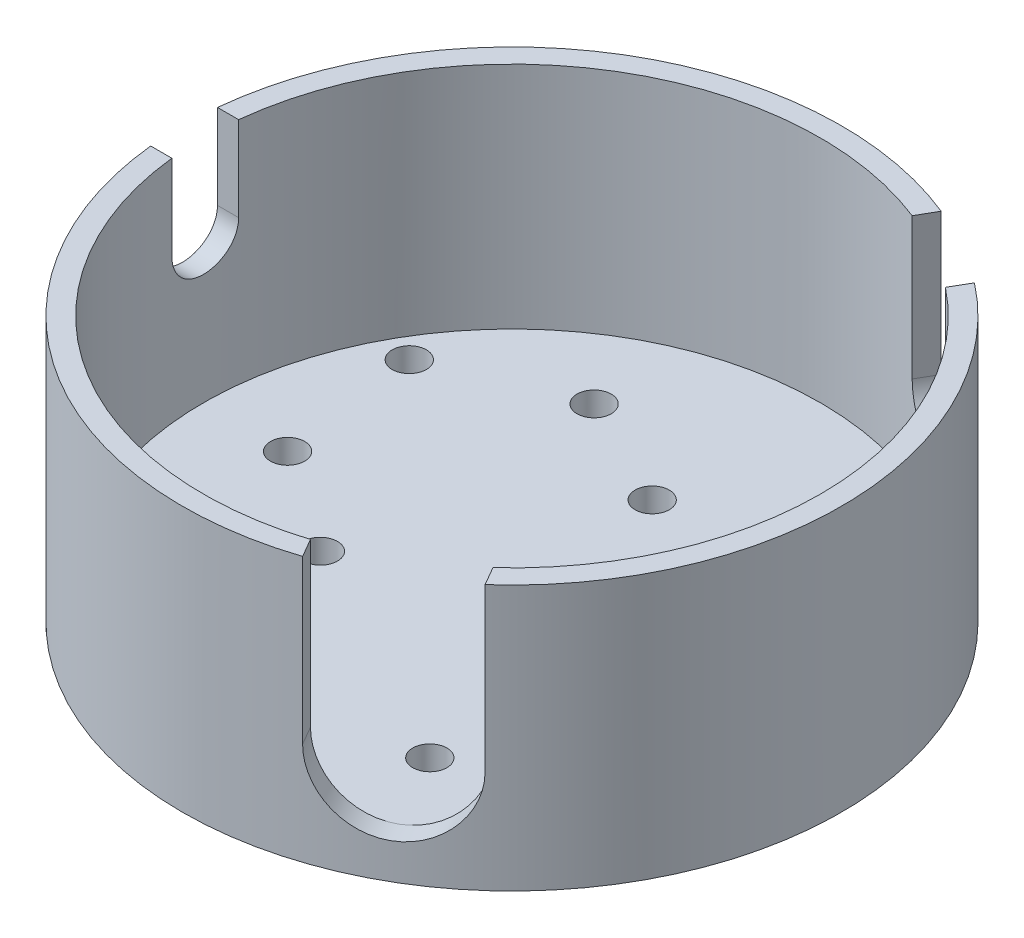
SolidWorks part; units mm, degrees
material "6061-T6 (SS)"
ref_plane "Front Plane" through (0, 0, 0) normal (0, 0, 1) x (1, 0, 0)
ref_plane "Top Plane" through (0, 0, 0) normal (0, 1, 0) x (1, 0, 0)
ref_plane "Right Plane" through (0, 0, 0) normal (1, 0, 0) x (0, 0, -1)
sketch "Sketch1" plane through (0, 0, 0) normal (0, 1, 0) x (1, 0, 0)
  circle A0 centre (0, 0) radius 23.5
  dimension "D1" = 47
extrude "Boss-Extrude1" add sketch "Sketch1" along normal blind 2.54
sketch "Sketch2" plane through (0, 2.54, 0) normal (0, 1, 0) x (1, 0, 0)
  circle A0 centre (0, 0) radius 10 construction
  circle A1 centre (0, 0) radius 23.5
  circle A2 centre (0, 0) radius 23.5
  point P1 (0, 10)
  point P5 (8.6603, -5)
  point P8 (-8.6603, -5)
  dimension "D2" = 20
  dimension "D1" = 0
  dimension "D3" = 3
hole_wizard "#2 Clearance Hole2" positions "3DSketch1" profile "Sketch3" hole size "#2" standard "Ansi Inch" end condition through all
sketch3d "3DSketch1"
  point P0 (0, 2.54, -10)
  point P3 (8.6603, 2.54, 5)
  point P6 (-8.6603, 2.54, 5)
sketch "Sketch3" plane through (0, 2.54, -10) normal (1, 0, 0) x (0, 0, 1)
  line L0 (0, 0) -> (0, 2.54)
  line L1 (0, 2.54) -> (1.2192, 2.54)
  line L2 (1.2192, 2.54) -> (1.2192, 0)
  line L5 (1.2192, 0) -> (0, 0)
  line L11 (0, -6.35) -> (0, 107.95) construction
  dimension "Thru Hole Dia." = 2.4384
  dimension "Thru Hole Depth" = 2.54
sketch "Sketch4" plane through (0, 2.54, 0) normal (0, 1, 0) x (1, 0, 0)
  circle A0 centre (0, 0) radius 22
  circle A1 centre (0, 0) radius 23.5
  circle A2 centre (0, 0) radius 23.5
  dimension "D1" = 0
  dimension "D2" = 1.5
extrude "Boss-Extrude2" add sketch "Sketch4" along normal blind 16.3576
sketch "Sketch5" plane through (0, 0, 0) normal (0, -1, 0) x (1, 0, 0)
  circle A0 centre (0, 0) radius 20 construction
  circle A1 centre (0, 0) radius 23.5
  circle A2 centre (0, 0) radius 23.5
  point P1 (0, 20)
  point P5 (17.3205, -10)
  point P8 (-17.3205, -10)
  dimension "D2" = 40
  dimension "D1" = 0
  dimension "D3" = 3
hole_wizard "#2 Clearance Hole1" positions "3DSketch2" profile "Sketch6" hole size "#2" standard "Ansi Inch" end condition through all
sketch3d "3DSketch2"
  point P0 (0, 0, 20)
  point P3 (17.3205, 0, -10)
  point P6 (-17.3205, 0, -10)
sketch "Sketch6" plane through (0, 0, 20) normal (1, 0, 0) x (0, 0, -1)
  line L0 (0, 0) -> (0, 18.8976)
  line L1 (0, 18.8976) -> (1.2192, 18.8976)
  line L2 (1.2192, 18.8976) -> (1.2192, 0)
  line L5 (1.2192, 0) -> (0, 0)
  line L11 (0, -6.35) -> (0, 107.95) construction
  dimension "Thru Hole Dia." = 2.4384
  dimension "Thru Hole Depth" = 18.8976
sketch "Sketch7" plane through (0, 0, 0) normal (0, -1, 0) x (1, 0, 0)
  line L0 (0, 0) -> (0, 16) construction
  line L1 (0, 0) -> (-8.6603, 5) construction
  line L2 (0, 0) -> (-8, 13.8564) construction
  circle A0 centre (0, 0) radius 16
  circle A1 centre (-8, 13.8564) radius 1.2192
  circle A2 centre (8.0005, 13.8573) radius 1.2192
  circle A3 centre (16.0015, 0.0009) radius 1.2192
  circle A4 centre (8.002, -13.8564) radius 1.2192
  circle A5 centre (-7.9985, -13.8573) radius 1.2192
  circle A6 centre (-15.9995, -0.0009) radius 1.2192
  circle A7 centre (0, 0) radius 0.75
  dimension "D1" = 32
  dimension "D3" = 2.4384
  dimension "D5" = 1.5
  dimension "D2" = 30
  dimension "D4" = 6
extrude "Cut-Extrude1" cut sketch "Sketch7" against normal through all contours A0 A6 | A0 A6 | A0 A1 | A0 A1 | A0 A2 | A0 A2 | A0 A3 | A0 A3 | A0 A4 | A0 A4 | A0 A5 | A0 A5 | A7
sketch "Sketch8" plane through (0, 0, 0) normal (0, -1, 0) x (1, 0, 0)
  line L0 (0, 0) -> (0, 23.5) construction
  line L1 (0, 0) -> (20.3516, -11.75) construction
  line L2 (0, 0) -> (11.75, -20.3516) construction
  line L3 (0, 0) -> (11.75, 20.3516) construction
  line L4 (0, 0) -> (-20.3516, -11.75) construction
  line L5 (0, 0) -> (-23.5, 0) construction
  circle A0 centre (0, 0) radius 23.5 construction
  dimension "D1" = 30
  dimension "D2" = 3
ref_plane "Plane1" through (11.75, 0, 20.3516) normal (0.5, 0, 0.866) x (0.866, 0, -0.5)
sketch "Sketch9" plane through (11.75, 0, 20.3516) normal (0.5, 0, 0.866) x (0.866, 0, -0.5)
  line L0 (0, 18.8976) -> (0, 7.3025) construction
  line L1 (23.5, 18.8976) -> (-23.5, 18.8976) construction
  line L2 (-4.7625, 7.3025) -> (-4.7625, 18.8976)
  line L3 (-4.7625, 18.8976) -> (4.7625, 18.8976)
  line L4 (22, 18.8976) -> (-22, 18.8976) construction
  line L5 (4.7625, 18.8976) -> (4.7625, 7.3025)
  line L6 (0, 0) -> (-20.3516, 0) construction
  arc A0 (-4.7625, 7.3025) -> (4.7625, 7.3025) centre (0, 7.3025) ccw
  dimension "D1" = 9.525
  dimension "D2" = 7.3025
extrude "Cut-Extrude2" cut sketch "Sketch9" against normal blind 10
ref_plane "Plane2" through (11.75, 0, -20.3516) normal (0.5, 0, -0.866) x (-0.866, 0, -0.5)
sketch "Sketch10" plane through (11.75, 0, -20.3516) normal (0.5, 0, -0.866) x (-0.866, 0, -0.5)
  line L0 (0, 18.8976) -> (0, 8.8138) construction
  line L1 (22, 18.8976) -> (-22, 18.8976) construction
  line L2 (0, 0) -> (20.3516, 0) construction
  line L3 (-3.2385, 8.8138) -> (-3.2385, 18.8976)
  line L4 (-3.2385, 18.8976) -> (3.2385, 18.8976)
  line L5 (3.2385, 18.8976) -> (3.2385, 8.8138)
  arc A0 (-3.2385, 8.8138) -> (3.2385, 8.8138) centre (0, 8.8138) ccw
  dimension "D1" = 6.477
  dimension "D2" = 8.8138
extrude "Cut-Extrude3" cut sketch "Sketch10" against normal blind 10
ref_plane "Plane3" through (-23.5, 0, 0) normal (-1, 0, 0) x (0, 0, 1)
sketch "Sketch11" plane through (-23.5, 0, 0) normal (-1, 0, 0) x (0, 0, 1)
  line L0 (0, 18.8976) -> (0, 12.846) construction
  line L1 (23.5, 18.8976) -> (-23.5, 18.8976) construction
  line L2 (0, 0) -> (20.3516, 0) construction
  line L3 (-2.3812, 12.846) -> (-2.3812, 18.8976)
  line L4 (-2.3812, 18.8976) -> (2.3813, 18.8976)
  line L5 (2.3813, 18.8976) -> (2.3813, 12.846)
  arc A0 (-2.3812, 12.846) -> (2.3813, 12.846) centre (0, 12.846) ccw
  dimension "D1" = 4.7625
  dimension "D2" = 12.846
extrude "Cut-Extrude4" cut sketch "Sketch11" against normal blind 10
